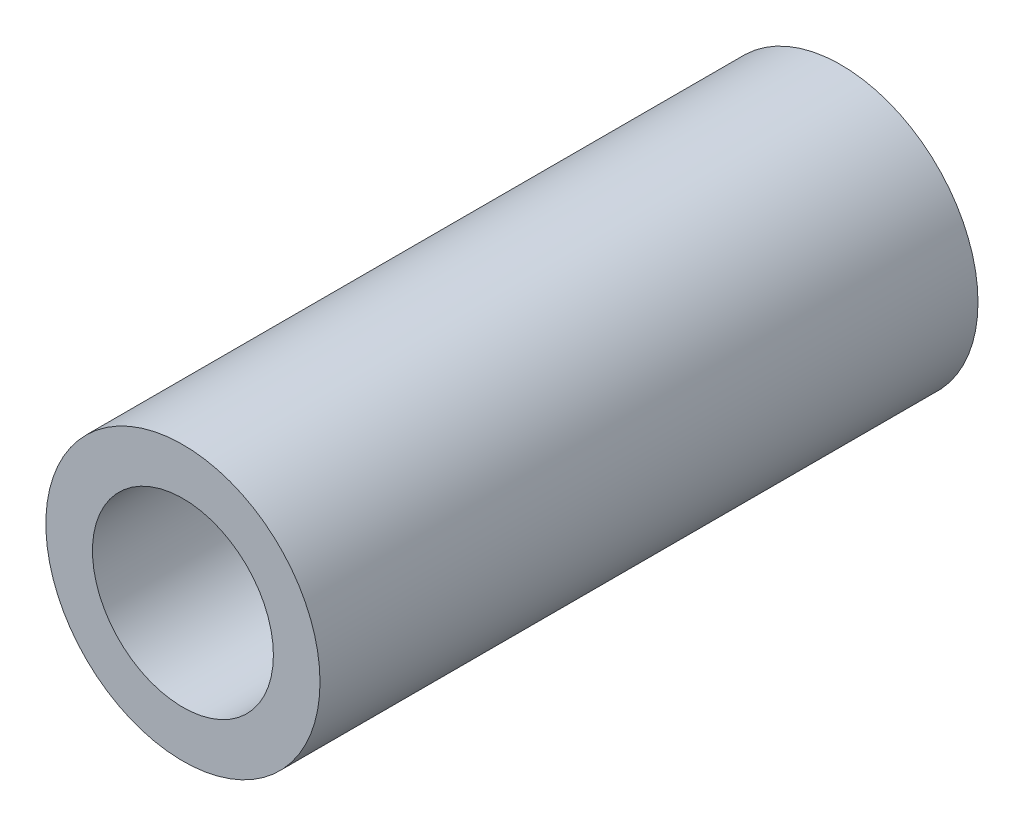
SolidWorks part; units mm, degrees
ref_plane "Plan de face" through (0, 0, 0) normal (0, 0, 1) x (1, 0, 0)
ref_plane "Plan de dessus" through (0, 0, 0) normal (0, 1, 0) x (1, 0, 0)
ref_plane "Plan de droite" through (0, 0, 0) normal (1, 0, 0) x (0, 0, -1)
sketch "Esquisse1" plane through (0, 0, 0) normal (0, 0, 1) x (1, 0, 0)
  circle A0 centre (0, 0) radius 2.5
extrude "Boss.-Extru.1" add sketch "Esquisse1" along normal blind 12
hole_wizard "Trou taraudé M41" positions "Esquisse4" profile "Esquisse3" tap size "M4" standard "Iso" end condition through all
sketch "Esquisse4" plane through (0, 0, 12) normal (0, 0, 1) x (1, 0, 0)
  point P0 (0, 0)
sketch "Esquisse3" plane through (0, 0, 12) normal (1, 0, 0) x (0, -1, 0)
  line L0 (0, 0) -> (0, 12)
  line L1 (0, 12) -> (1.65, 12)
  line L2 (1.65, 12) -> (1.65, 0)
  line L5 (1.65, 0) -> (0, 0)
  line L11 (0, -6.35) -> (0, 107.95) construction
  dimension "Diamètre du trou pour taraudage jusqu'au prochain" = 3.3
  dimension "Profondeur du trou pour taraudage jusqu'au prochain" = 12
cosmetic thread "Filetage de perçage1"
